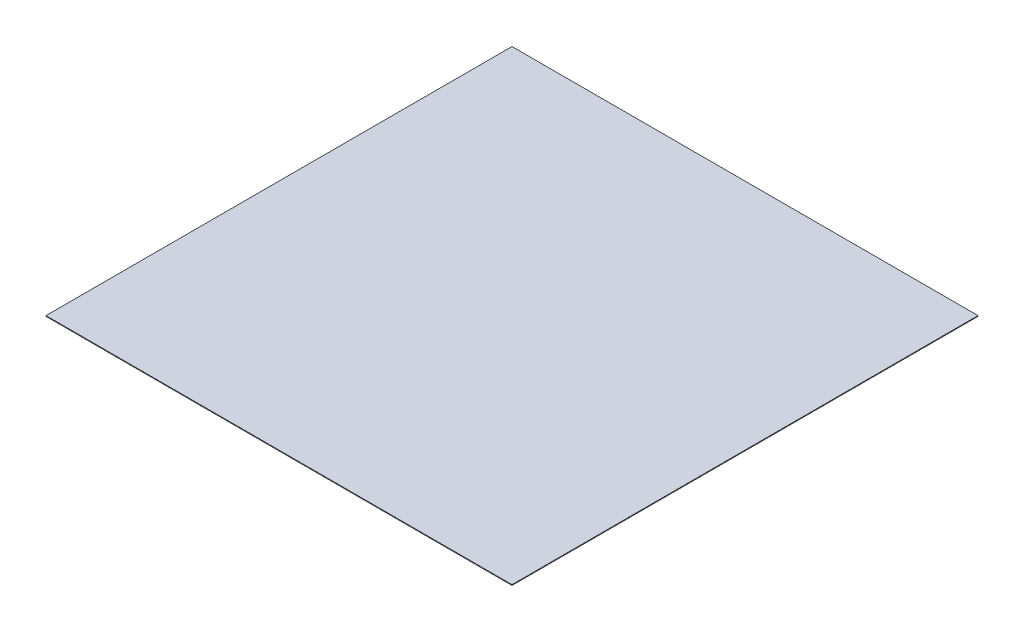
SolidWorks part; units mm, degrees
ref_plane "Front Plane" through (0, 0, 0) normal (0, 0, 1) x (1, 0, 0)
ref_plane "Top Plane" through (0, 0, 0) normal (0, 1, 0) x (1, 0, 0)
ref_plane "Right Plane" through (0, 0, 0) normal (1, 0, 0) x (0, 0, -1)
sketch "Sketch1" plane through (0, 0, 0) normal (0, 1, 0) x (1, 0, 0)
  line L1 (-662.5, -662.5) -> (662.5, -662.5)
  line L2 (-662.5, -662.5) -> (-662.5, 662.5)
  line L3 (-662.5, 662.5) -> (662.5, 662.5)
  line L4 (662.5, -662.5) -> (662.5, 662.5)
  line L5 (-662.5, -662.5) -> (662.5, 662.5) construction
  line L6 (-662.5, 662.5) -> (662.5, -662.5) construction
  point P0 (0, 0)
  dimension "D1" = 1325
  dimension "D2" = 1325
extrude "Boss-Extrude1" add sketch "Sketch1" along normal blind 2
